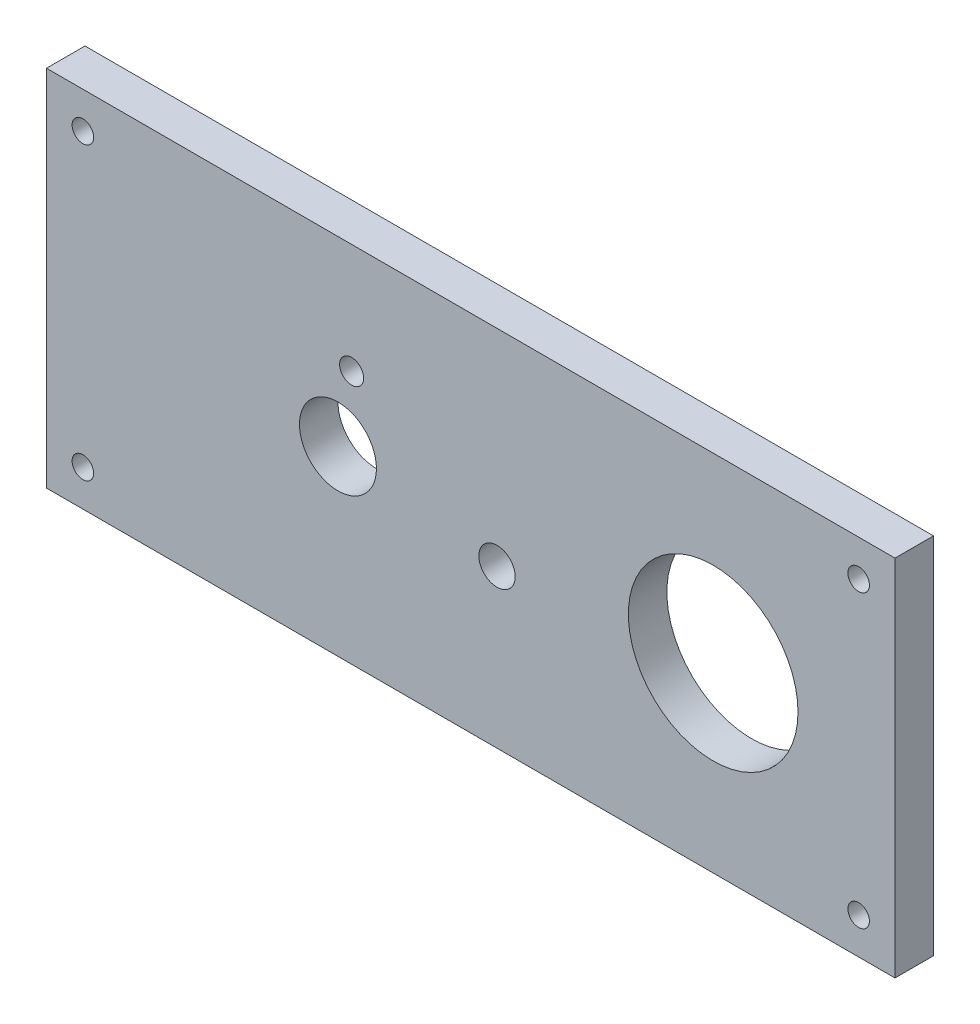
SolidWorks part; units mm, degrees
ref_plane "Front Plane" through (0, 0, 0) normal (0, 0, 1) x (1, 0, 0)
ref_plane "Top Plane" through (0, 0, 0) normal (0, 1, 0) x (1, 0, 0)
ref_plane "Right Plane" through (0, 0, 0) normal (1, 0, 0) x (0, 0, -1)
sketch "Sketch1" plane through (0, 0, 0) normal (0, 0, 1) x (1, 0, 0)
  line L0 (70, 15) -> (0, 15) construction
  line L1 (0, 0) -> (70, 0)
  line L2 (0, 0) -> (0, 30)
  line L3 (0, 30) -> (70, 30)
  line L4 (70, 0) -> (70, 30)
  circle A0 centre (55, 15) radius 6.9977
  circle A1 centre (37.1667, 13) radius 1.4986
  circle A2 centre (25.1698, 20.9334) radius 0.9906
  circle A3 centre (37.1667, 13) radius 11.4777 construction
  circle A4 centre (25.1698, 20.9334) radius 7.1501 construction
  circle A5 centre (55, 15) radius 12.827 construction
  circle A6 centre (16, 15) radius 14 construction
  circle A7 centre (37.1667, 13) radius 5.1181 construction
  point P7 (55, 15)
  point P8 (37.1667, 13)
  point P9 (25.1698, 20.9334)
  point P19 (16, 15)
  dimension "D6" = 13.9954
  dimension "D7" = 2.9972
  dimension "D8" = 1.9812
  dimension "D9" = 25.654
  dimension "D10" = 22.9553
  dimension "D11" = 14.3002
  dimension "D13" = 28
  dimension "D14" = 10.2362
  dimension "D1" = 17.9451
  dimension "D2" = 14.3828
  dimension "D3" = 30
  dimension "D4" = 70
  dimension "D5" = 15
  dimension "D12" = 10.922
  dimension "D15" = 16
  dimension "D16" = 13
extrude "Boss-Extrude2" add sketch "Sketch1" along normal blind 3.175
hole_wizard "#2-56 Tapped Hole1" positions "Sketch3" profile "Sketch2" tap size "#2-56" standard "ANSI Inch" end condition through all
sketch "Sketch3" plane through (0, 0, 3.175) normal (0, 0, 1) x (1, 0, 0)
  line L0 (67, 30) -> (67, 0) construction
  line L1 (70, 30) -> (0, 30) construction
  line L2 (0, 0) -> (70, 0) construction
  line L4 (70, 0) -> (70, 30) construction
  line L6 (3, 30) -> (3, 0) construction
  line L8 (0, 30) -> (0, 0) construction
  point P12 (67, 27)
  point P14 (67, 3)
  point P28 (3, 27)
  point P30 (3, 3)
  dimension "D1" = 3
  dimension "D2" = 3
  dimension "D3" = 3
  dimension "D4" = 3
  dimension "D5" = 3
  dimension "D6" = 3
sketch "Sketch2" plane through (67, 27, 3.175) normal (1, 0, 0) x (0, -1, 0)
  line L0 (0, 0) -> (0, 3.175)
  line L1 (0, 3.175) -> (0.889, 3.175)
  line L2 (0.889, 3.175) -> (0.889, 0)
  line L5 (0.889, 0) -> (0, 0)
  line L11 (0, -6.35) -> (0, 107.95) construction
  dimension "Thread Major Dia." = 1.778
  dimension "Thru Tap Drill Depth" = 3.175
sketch "Sketch4" plane through (0, 0, 3.175) normal (0, 0, 1) x (1, 0, 0)
  line L0 (0, 15) -> (70, 15) construction
  line L1 (0, 30) -> (0, 0) construction
  line L2 (70, 0) -> (70, 30) construction
  circle A0 centre (24.0438, 15) radius 3.175
  circle A1 centre (55, 15) radius 6.9977 construction
  dimension "D1" = 6.35
  dimension "D2" = 30.9562
extrude "Cut-Extrude1" cut sketch "Sketch4" against normal through all
